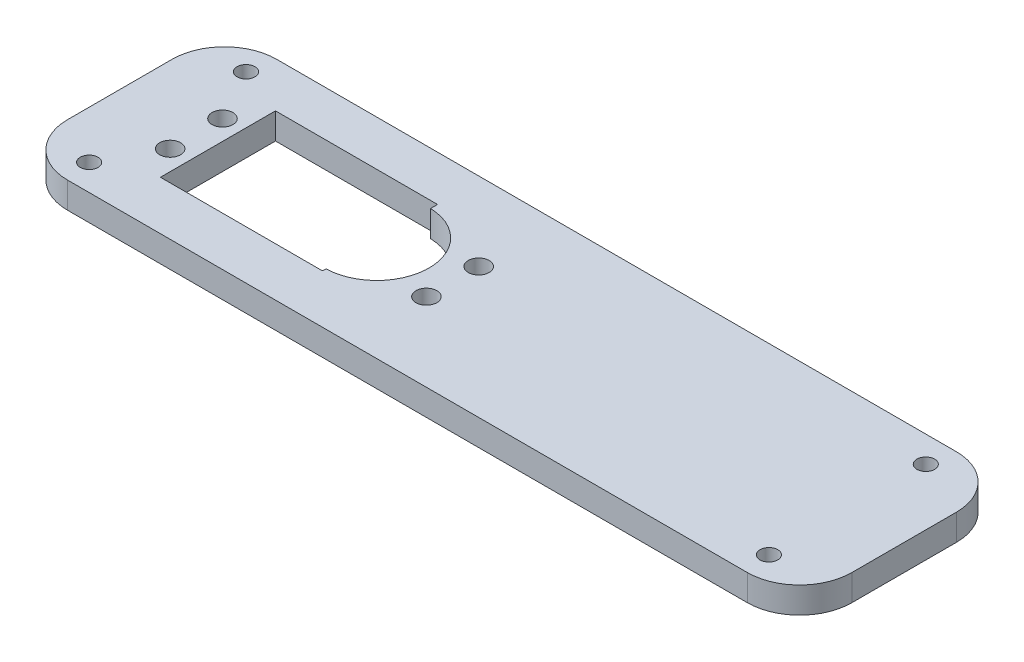
SolidWorks part; units mm, degrees
ref_plane "Front Plane" through (0, 0, 0) normal (0, 0, 1) x (1, 0, 0)
ref_plane "Top Plane" through (0, 0, 0) normal (0, 1, 0) x (1, 0, 0)
ref_plane "Right Plane" through (0, 0, 0) normal (1, 0, 0) x (0, 0, -1)
sketch "Sketch9" plane through (0, 0, 0) normal (0, 1, 0) x (1, 0, 0)
  line L5 (-49.1323, 20) -> (100.8677, 20)
  line L6 (-49.1323, 20) -> (-49.1323, -20)
  line L7 (-49.1323, -20) -> (100.8677, -20)
  line L8 (100.8677, 20) -> (100.8677, -20)
  line L9 (-49.1323, 20) -> (100.8677, -20) construction
  line L10 (-49.1323, -20) -> (100.8677, 20) construction
  point P0 (25.8677, 0)
  dimension "D1" = 40
  dimension "D2" = 150
extrude "Boss-Extrude5" add sketch "Sketch9" along normal blind 5 separate body
sketch "Sketch10" plane through (0, 5, 0) normal (0, 1, 0) x (1, 0, 0)
  line L4 (-30.7077, 11.3457) -> (-30.711, -10.6563)
  line L5 (-30.711, -10.6563) -> (0.2923, -10.661)
  line L6 (0.2923, -10.661) -> (0.2923, 11.339)
  line L7 (0.2923, 11.339) -> (-30.7077, 11.3457)
  circle A0 centre (14.5, 5) radius 2
  circle A1 centre (14.5, -5) radius 2
  circle A2 centre (-34.5, 5) radius 2
  circle A3 centre (-34.5, -5) radius 2
  circle A4 centre (0, 0) radius 10
  circle A5 centre (-13, 0) radius 8
  dimension "D1" = 16
  dimension "D2" = 10
  dimension "D3" = 10
  dimension "D6" = 20
  dimension "D7" = 2
  dimension "D9" = 14.5
  dimension "D10" = 34.5
  dimension "D11" = 13
  dimension "D4" = 31
  dimension "D5" = 22.002
  dimension "D8" = 14.5
  dimension "D12" = 5
  dimension "D13" = 11.339
  dimension "D14" = 30.7094
extrude "Cut-Extrude5" cut sketch "Sketch10" against normal through all contours A5 A4 L6 L7 L4 L5 | L6 A4 | A5 A4 L6 | A4 A5 | A4 A5 | A0 | A1 | A2 | A3
sketch "Sketch11" plane through (0, 5, 0) normal (0, 1, 0) x (1, 0, 0)
  circle A0 centre (-40, 15) radius 1.7
  circle A1 centre (90, 15) radius 1.7
  circle A2 centre (90, -15) radius 1.7
  circle A3 centre (-40, -15) radius 1.7
  dimension "D1" = 3.4
  dimension "D3" = 130
  dimension "D5" = 30
  dimension "D2" = 40
  dimension "D4" = 15
extrude "Cut-Extrude6" cut sketch "Sketch11" against normal through all
fillet "Fillet1" radius 10 4 edges at (100.8677, 2.5, 20) (-49.1323, 2.5, 20) (-49.1323, 2.5, -20) (100.8677, 2.5, -20)
sketch "Sketch12" plane through (0, 5, 0) normal (0, 1, 0) x (1, 0, 0)
  line L0 (-1.6323, 20) -> (-1.6323, -20)
  line L4 (-49.1323, 10) -> (-49.1323, -10) construction
  dimension "D1" = 47.5
